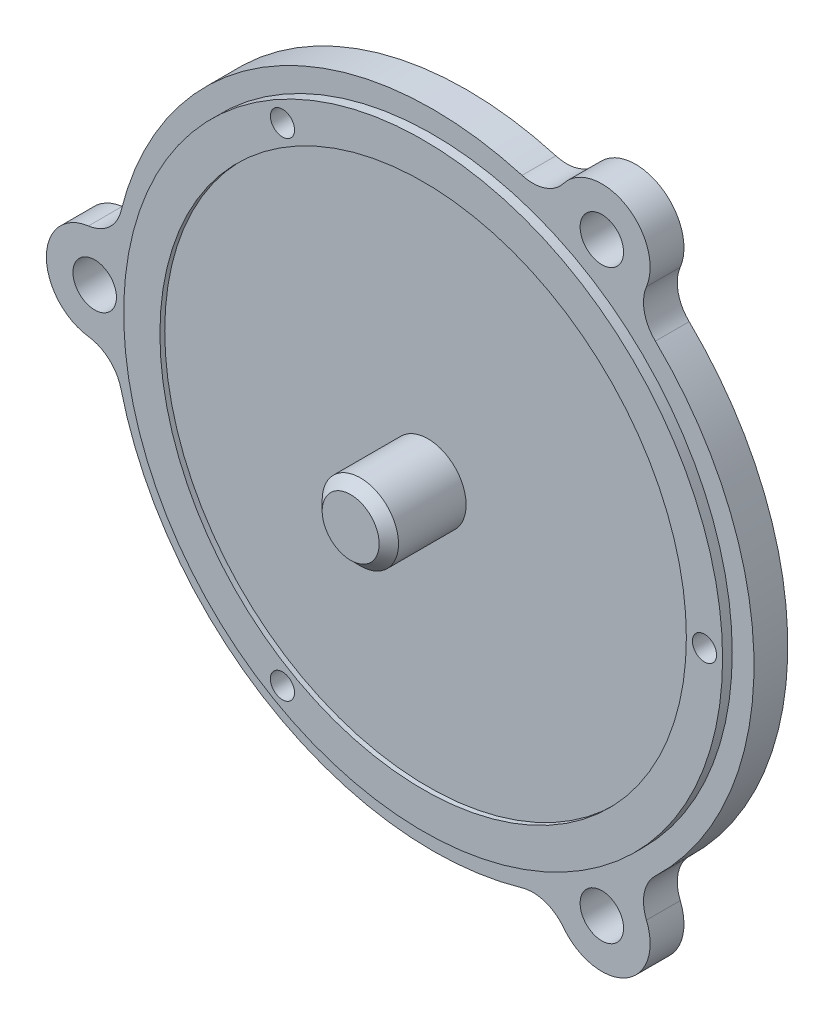
SolidWorks part; units mm, degrees
ref_plane "Front" through (0, 0, 0) normal (0, 0, 1) x (1, 0, 0)
ref_plane "Top" through (0, 0, 0) normal (0, 1, 0) x (1, 0, 0)
ref_plane "Right" through (0, 0, 0) normal (1, 0, 0) x (0, 0, -1)
sketch "Esquisse1" plane through (0, 0, 0) normal (0, 0, 1) x (1, 0, 0)
  circle A0 centre (0, 0) radius 31.25
  dimension "D1" = 62.5
extrude "Boss.-Extru.1" add sketch "Esquisse1" along normal blind 2
sketch "Esquisse2" plane through (0, 0, 2) normal (0, 0, 1) x (1, 0, 0)
  circle A0 centre (0, 0) radius 33.25
  circle A1 centre (0, 0) radius 31.25 construction
  circle A2 centre (0, 0) radius 31.25
  dimension "D1" = 2
extrude "Boss.-Extru.2" add sketch "Esquisse2" along normal blind 25.5 and the other way up to surface (2 mm away) other way up to face at (31.25, 0, 0)
sketch "Esquisse3" plane through (0, 0, 2) normal (0, 0, 1) x (1, 0, 0)
  circle A0 centre (0, 0) radius 7.95
  dimension "D1" = 15.9
extrude "Boss.-Extru.3" add sketch "Esquisse3" along normal blind 7.5
sketch "Esquisse4" plane through (0, 0, 9.5) normal (0, 0, 1) x (1, 0, 0)
  circle A0 centre (0, 0) radius 3.95
  dimension "D1" = 7.9
extrude "Boss.-Extru.4" add sketch "Esquisse4" along normal blind 8
chamfer "Chanfrein1" distance 1 angle 45 2 edges at (7.95, 0, 9.5) (3.95, 0, 17.5)
sketch "Esquisse5" plane through (0, 0, 27.5) normal (0, 0, 1) x (1, 0, 0)
  line L0 (-35, 0) -> (0, 0) construction
  arc A0 (-32.9366, -4.5544) -> (-32.9366, 4.5544) centre (-35, 0) cw
  circle A1 centre (0, 0) radius 33.25 construction
  arc A2 (-32.9366, 4.5544) -> (-32.9366, -4.5544) centre (0, 0) ccw
  dimension "D1" = 5
  dimension "D2" = 35
extrude "Boss.-Extru.5" add sketch "Esquisse5" against normal up to surface (27.5 mm away)
sketch "Esquisse6" plane through (0, 0, 27.5) normal (0, 0, 1) x (1, 0, 0)
  circle A0 centre (-35, 0) radius 1.75
  dimension "D1" = 3.5
extrude "Enlèv. mat.-Extru.1" cut sketch "Esquisse6" against normal blind 10
fillet "Congé1" radius 4 2 edges at (-32.9366, -4.5544, 13.75) (-32.9366, 4.5544, 13.75)
pattern_circular "Répétition circulaire2" count 3 over 360 about axis through (0, 0, 0) along (0, 0, 1) of "Boss.-Extru.5", "Enlèv. mat.-Extru.1", "Congé1"
sketch "Esquisse7" plane through (0, 0, 27.5) normal (0, 0, 1) x (1, 0, 0)
  arc A12 (-35.6473, 4.9579) -> (-35.6473, -4.9579) centre (-35, 0) ccw
  arc A13 (-32.2817, -7.9659) -> (-35.6473, -4.9579) centre (-36.1652, -8.9243) ccw
  arc A14 (-32.2817, -7.9659) -> (9.2421, -31.9397) centre (0, 0) ccw
  arc A15 (13.53, -33.3504) -> (9.2421, -31.9397) centre (10.354, -35.7821) ccw
  arc A16 (13.53, -33.3504) -> (22.1173, -28.3925) centre (17.5, -30.3109) ccw
  arc A17 (23.0395, -23.9738) -> (22.1173, -28.3925) centre (25.8112, -26.8578) ccw
  arc A18 (23.0395, -23.9738) -> (23.0395, 23.9738) centre (0, 0) ccw
  arc A19 (22.1173, 28.3925) -> (23.0395, 23.9738) centre (25.8112, 26.8578) ccw
  arc A20 (22.1173, 28.3925) -> (13.53, 33.3504) centre (17.5, 30.3109) ccw
  arc A21 (9.2421, 31.9397) -> (13.53, 33.3504) centre (10.354, 35.7821) ccw
  arc A22 (9.2421, 31.9397) -> (-32.2817, 7.9659) centre (0, 0) ccw
  arc A23 (-35.6473, 4.9579) -> (-32.2817, 7.9659) centre (-36.1652, 8.9243) ccw
  arc A24 (-35.6473, 4.9579) -> (-35.6473, -4.9579) centre (-35, 0) ccw
  arc A25 (-32.2817, -7.9659) -> (-35.6473, -4.9579) centre (-36.1652, -8.9243) ccw
  arc A26 (-32.2817, -7.9659) -> (9.2421, -31.9397) centre (0, 0) ccw
  arc A27 (13.53, -33.3504) -> (9.2421, -31.9397) centre (10.354, -35.7821) ccw
  arc A28 (13.53, -33.3504) -> (22.1173, -28.3925) centre (17.5, -30.3109) ccw
  arc A29 (23.0395, -23.9738) -> (22.1173, -28.3925) centre (25.8112, -26.8578) ccw
  arc A30 (23.0395, -23.9738) -> (23.0395, 23.9738) centre (0, 0) ccw
  arc A31 (22.1173, 28.3925) -> (23.0395, 23.9738) centre (25.8112, 26.8578) ccw
  arc A32 (22.1173, 28.3925) -> (13.53, 33.3504) centre (17.5, 30.3109) ccw
  arc A33 (9.2421, 31.9397) -> (13.53, 33.3504) centre (10.354, 35.7821) ccw
  arc A34 (9.2421, 31.9397) -> (-32.2817, 7.9659) centre (0, 0) ccw
  arc A35 (-35.6473, 4.9579) -> (-32.2817, 7.9659) centre (-36.1652, 8.9243) ccw
  dimension "D1" = 0
extrude "Enlèv. mat.-Extru.2" cut sketch "Esquisse7" against normal blind 25.5
sketch "Esquisse8" plane through (0, 0, 2) normal (0, 0, 1) x (1, 0, 0)
  circle A0 centre (0, 0) radius 3.95
  dimension "D1" = 7.9
extrude "Boss.-Extru.6" add sketch "Esquisse8" along normal blind 8
sketch "Esquisse9" plane through (0, 0, 2) normal (0, 0, 1) x (1, 0, 0)
  circle A0 centre (-35, 0) radius 2.25
  circle A1 centre (17.5, 30.3109) radius 2.25
  circle A2 centre (17.5, -30.3109) radius 2.25
  dimension "D1" = 4.5
extrude "Enlèv. mat.-Extru.3" cut sketch "Esquisse9" against normal through all
chamfer "Chanfrein2" distance 1 angle 45 1 edges at (3.95, 0, 10)
sketch "Esquisse10" plane through (0, 0, 2) normal (0, 0, 1) x (1, 0, 0)
  circle A0 centre (0, 0) radius 31
  circle A1 centre (0, 0) radius 27.25
  dimension "D1" = 62
  dimension "D2" = 54.5
extrude "Boss.-Extru.7" add sketch "Esquisse10" along normal blind 0.5
sketch "Esquisse11" plane through (0, 0, 2) normal (0, 0, 1) x (1, 0, 0)
  circle A12 centre (0, 0) radius 31 construction
  circle A13 centre (0, 0) radius 31
  arc A24 (-35.6473, 4.9579) -> (-32.2817, 7.9659) centre (-36.1652, 8.9243) ccw
  arc A25 (-35.6473, 4.9579) -> (-35.6473, -4.9579) centre (-35, 0) ccw
  arc A26 (-32.2817, -7.9659) -> (-35.6473, -4.9579) centre (-36.1652, -8.9243) ccw
  arc A27 (-32.2817, -7.9659) -> (9.2421, -31.9397) centre (0, 0) ccw
  arc A28 (13.53, -33.3504) -> (9.2421, -31.9397) centre (10.354, -35.7821) ccw
  arc A29 (13.53, -33.3504) -> (22.1173, -28.3925) centre (17.5, -30.3109) ccw
  arc A30 (23.0395, -23.9738) -> (22.1173, -28.3925) centre (25.8112, -26.8578) ccw
  arc A31 (23.0395, -23.9738) -> (23.0395, 23.9738) centre (0, 0) ccw
  arc A32 (22.1173, 28.3925) -> (23.0395, 23.9738) centre (25.8112, 26.8578) ccw
  arc A33 (22.1173, 28.3925) -> (13.53, 33.3504) centre (17.5, 30.3109) ccw
  arc A34 (9.2421, 31.9397) -> (13.53, 33.3504) centre (10.354, 35.7821) ccw
  arc A35 (9.2421, 31.9397) -> (-32.2817, 7.9659) centre (0, 0) ccw
  arc A36 (-35.6473, 4.9579) -> (-32.2817, 7.9659) centre (-36.1652, 8.9243) ccw
  arc A37 (-35.6473, 4.9579) -> (-35.6473, -4.9579) centre (-35, 0) ccw
  arc A38 (-32.2817, -7.9659) -> (-35.6473, -4.9579) centre (-36.1652, -8.9243) ccw
  arc A39 (-32.2817, -7.9659) -> (9.2421, -31.9397) centre (0, 0) ccw
  arc A40 (13.53, -33.3504) -> (9.2421, -31.9397) centre (10.354, -35.7821) ccw
  arc A41 (13.53, -33.3504) -> (22.1173, -28.3925) centre (17.5, -30.3109) ccw
  arc A42 (23.0395, -23.9738) -> (22.1173, -28.3925) centre (25.8112, -26.8578) ccw
  arc A43 (23.0395, -23.9738) -> (23.0395, 23.9738) centre (0, 0) ccw
  arc A44 (22.1173, 28.3925) -> (23.0395, 23.9738) centre (25.8112, 26.8578) ccw
  arc A45 (22.1173, 28.3925) -> (13.53, 33.3504) centre (17.5, 30.3109) ccw
  arc A46 (9.2421, 31.9397) -> (13.53, 33.3504) centre (10.354, 35.7821) ccw
  arc A47 (9.2421, 31.9397) -> (-32.2817, 7.9659) centre (0, 0) ccw
  dimension "D1" = 0
extrude "Enlèv. mat.-Extru.4" cut sketch "Esquisse11" against normal blind 0.5
sketch "Esquisse12" plane through (0, 0, 0) normal (0, 0, -1) x (-1, 0, 0)
  circle A0 centre (35, 0) radius 2.25 construction
  circle A1 centre (-17.5, -30.3109) radius 2.25 construction
  circle A2 centre (-17.5, 30.3109) radius 2.25 construction
  circle A3 centre (35, 0) radius 2.25
  circle A4 centre (-17.5, -30.3109) radius 2.25
  circle A5 centre (-17.5, 30.3109) radius 2.25
  arc A12 (35.6473, -4.9579) -> (35.6473, 4.9579) centre (35, 0) ccw
  arc A13 (32.2817, 7.9659) -> (35.6473, 4.9579) centre (36.1652, 8.9243) ccw
  arc A14 (32.2817, 7.9659) -> (-9.2421, 31.9397) centre (0, 0) ccw
  arc A15 (-13.53, 33.3504) -> (-9.2421, 31.9397) centre (-10.354, 35.7821) ccw
  arc A16 (-13.53, 33.3504) -> (-22.1173, 28.3925) centre (-17.5, 30.3109) ccw
  arc A17 (-23.0395, 23.9738) -> (-22.1173, 28.3925) centre (-25.8112, 26.8578) ccw
  arc A18 (-23.0395, 23.9738) -> (-23.0395, -23.9738) centre (0, 0) ccw
  arc A19 (-22.1173, -28.3925) -> (-23.0395, -23.9738) centre (-25.8112, -26.8578) ccw
  arc A20 (-22.1173, -28.3925) -> (-13.53, -33.3504) centre (-17.5, -30.3109) ccw
  arc A21 (-9.2421, -31.9397) -> (-13.53, -33.3504) centre (-10.354, -35.7821) ccw
  arc A22 (-9.2421, -31.9397) -> (32.2817, -7.9659) centre (0, 0) ccw
  arc A23 (35.6473, -4.9579) -> (32.2817, -7.9659) centre (36.1652, -8.9243) ccw
  arc A24 (35.6473, -4.9579) -> (35.6473, 4.9579) centre (35, 0) ccw
  arc A25 (32.2817, 7.9659) -> (35.6473, 4.9579) centre (36.1652, 8.9243) ccw
  arc A26 (32.2817, 7.9659) -> (-9.2421, 31.9397) centre (0, 0) ccw
  arc A27 (-13.53, 33.3504) -> (-9.2421, 31.9397) centre (-10.354, 35.7821) ccw
  arc A28 (-13.53, 33.3504) -> (-22.1173, 28.3925) centre (-17.5, 30.3109) ccw
  arc A29 (-23.0395, 23.9738) -> (-22.1173, 28.3925) centre (-25.8112, 26.8578) ccw
  arc A30 (-23.0395, 23.9738) -> (-23.0395, -23.9738) centre (0, 0) ccw
  arc A31 (-22.1173, -28.3925) -> (-23.0395, -23.9738) centre (-25.8112, -26.8578) ccw
  arc A32 (-22.1173, -28.3925) -> (-13.53, -33.3504) centre (-17.5, -30.3109) ccw
  arc A33 (-9.2421, -31.9397) -> (-13.53, -33.3504) centre (-10.354, -35.7821) ccw
  arc A34 (-9.2421, -31.9397) -> (32.2817, -7.9659) centre (0, 0) ccw
  arc A35 (35.6473, -4.9579) -> (32.2817, -7.9659) centre (36.1652, -8.9243) ccw
  point P0 (0, 0)
  dimension "D1" = 0
extrude "Boss.-Extru.8" add sketch "Esquisse12" along normal blind 2
sketch "Esquisse13" plane through (0, 0, 2.5) normal (0, 0, 1) x (1, 0, 0)
  line L0 (-14.5625, 25.223) -> (-13.625, 23.5992) construction
  line L1 (-14.5625, 25.223) -> (-15.5, 26.8468) construction
  line L2 (-35, 0) -> (-14.5625, 25.223) construction
  line L3 (-14.5625, 25.223) -> (17.5, 30.3109) construction
  line L4 (-13.625, 23.5992) -> (0, 0) construction
  line L5 (29.125, 0) -> (27.25, 0) construction
  line L6 (29.125, 0) -> (31, 0) construction
  line L7 (-14.5625, -25.223) -> (-13.625, -23.5992) construction
  line L8 (-14.5625, -25.223) -> (-15.5, -26.8468) construction
  circle A0 centre (-14.5625, 25.223) radius 1.25
  circle A1 centre (0, 0) radius 27.25 construction
  circle A2 centre (0, 0) radius 31 construction
  circle A3 centre (29.125, 0) radius 1.25
  circle A4 centre (-14.5625, -25.223) radius 1.25
  point P9 (0, 0)
  point P15 (-14.5625, -25.223)
  point P24 (0, 0)
  dimension "D1" = 2.5
  dimension "D2" = 3
extrude "Enlèv. mat.-Extru.5" cut sketch "Esquisse13" against normal through all
